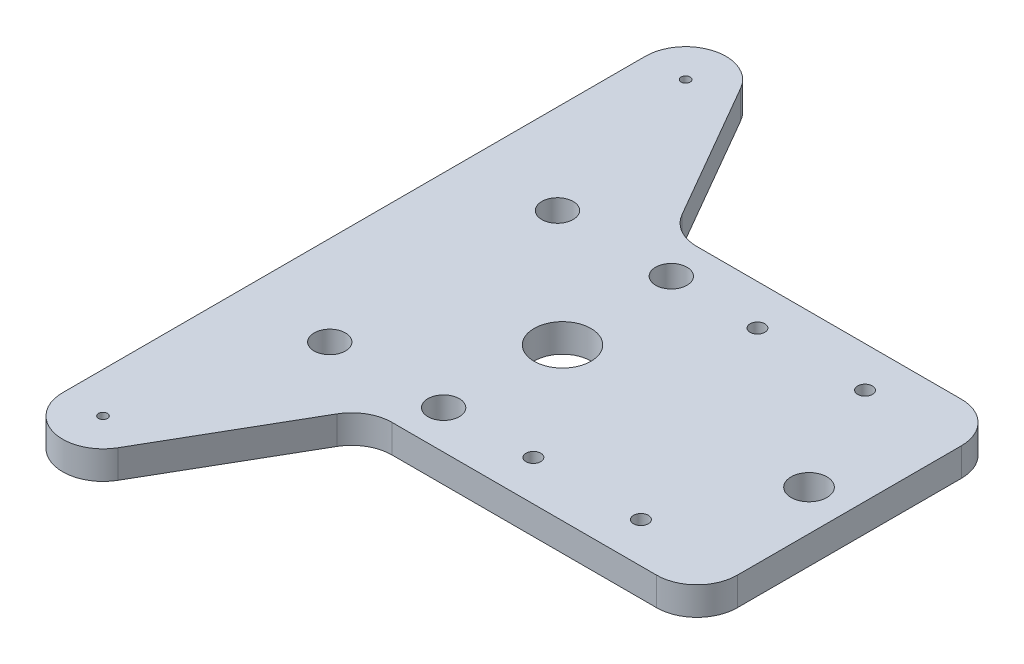
SolidWorks part; units mm, degrees
ref_plane "Front Plane" through (0, 0, 0) normal (0, 0, 1) x (1, 0, 0)
ref_plane "Top Plane" through (0, 0, 0) normal (0, 1, 0) x (1, 0, 0)
ref_plane "Right Plane" through (0, 0, 0) normal (1, 0, 0) x (0, 0, -1)
sketch "Sketch1" plane through (0, 0, 0) normal (0, 1, 0) x (1, 0, 0)
  line L0 (0, 0) -> (101.5278, 0) construction
  line L1 (0, -65) -> (0, 65)
  line L2 (16.7942, 69.5) -> (34.6921, 38.5)
  line L3 (42.4863, 34) -> (101.5278, 34)
  line L4 (46.5278, 0) -> (9, 65) construction
  line L5 (20, 25.4) -> (45.4, 25.4) construction
  line L6 (110.5278, 25) -> (110.5278, -25)
  line L7 (101.5278, 34) -> (101.5278, -34) construction
  line L8 (20, -25.4) -> (45.4, -25.4) construction
  line L9 (46.5278, 0) -> (9, -65) construction
  line L10 (42.4863, -34) -> (101.5278, -34)
  line L11 (16.7942, -69.5) -> (34.6921, -38.5)
  arc A0 (0, 65) -> (16.7942, 69.5) centre (9, 65) cw
  arc A1 (101.5278, 34) -> (110.5278, 25) centre (101.5278, 25) cw
  circle A2 centre (9, 65) radius 1
  arc A3 (34.6921, -38.5) -> (42.4863, -34) centre (42.4863, -43) cw
  circle A4 centre (46.5278, 0) radius 6.35
  circle A5 centre (101.5278, 0) radius 4
  circle A6 centre (20, 25.4) radius 3.5
  circle A7 centre (45.4, 25.4) radius 3.5
  arc A8 (34.6921, 38.5) -> (42.4863, 34) centre (42.4863, 43) ccw
  circle A9 centre (45.4, -25.4) radius 3.5
  circle A10 centre (20, -25.4) radius 3.5
  circle A11 centre (9, -65) radius 1
  arc A12 (101.5278, -34) -> (110.5278, -25) centre (101.5278, -25) ccw
  arc A13 (0, -65) -> (16.7942, -69.5) centre (9, -65) ccw
  circle A14 centre (89.0278, -25) radius 1.65
  circle A15 centre (65.0278, -25) radius 1.65
  circle A16 centre (65.0278, 25) radius 1.65
  circle A17 centre (89.0278, 25) radius 1.65
  point P37 (110.5278, 0)
  dimension "D2" = 2
  dimension "D3" = 9
  dimension "D5" = 6.35
  dimension "D8" = 4
  dimension "D9" = 25.4
  dimension "D12" = 7
  dimension "D14" = 3.3
  dimension "D7" = 34
  dimension "D4" = 65
  dimension "D6" = 55
  dimension "D10" = 25.4
  dimension "D11" = 20
  dimension "D13" = 60
  dimension "D15" = 24
  dimension "D16" = 25
  dimension "D17" = 21.5
extrude "Boss-Extrude3" add sketch "Sketch1" along normal blind 6.3
